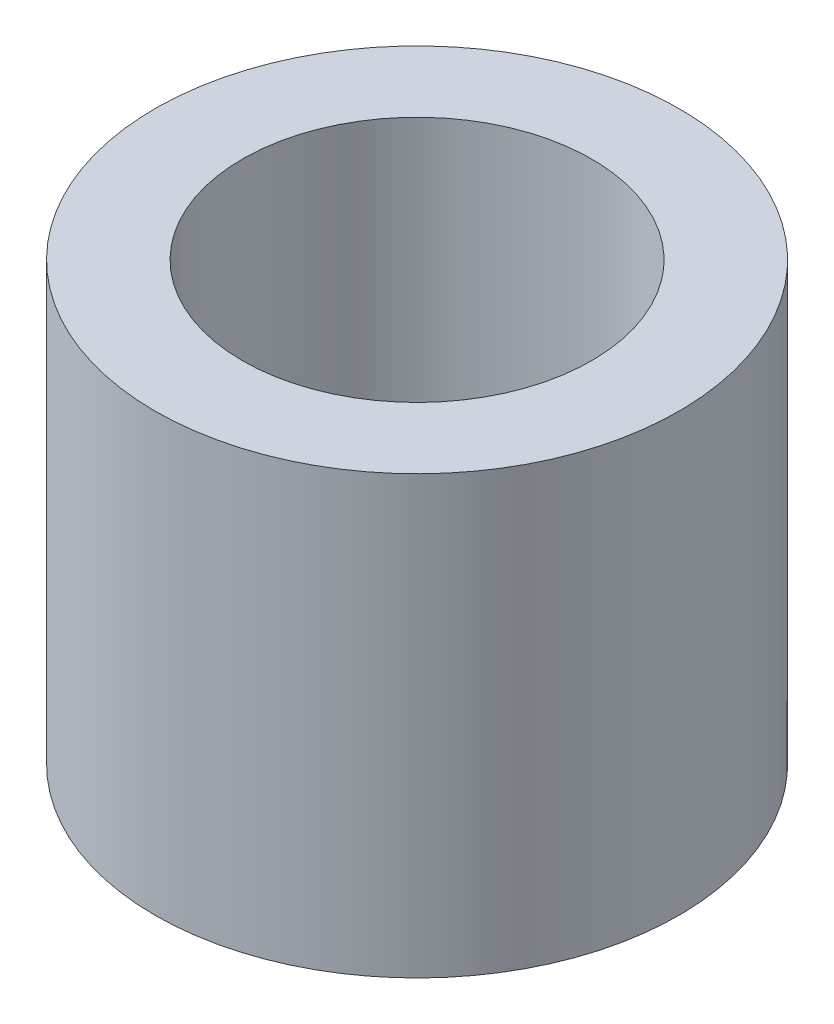
SolidWorks part; units mm, degrees
material "Brass"
ref_plane "Front Plane" through (0, 0, 0) normal (0, 0, 1) x (1, 0, 0)
ref_plane "Top Plane" through (0, 0, 0) normal (0, 1, 0) x (1, 0, 0)
ref_plane "Right Plane" through (0, 0, 0) normal (1, 0, 0) x (0, 0, -1)
sketch "Sketch2" plane through (0, 0, 0) normal (0, 1, 0) x (1, 0, 0)
  circle A0 centre (0, 0) radius 4
  circle A1 centre (0, 0) radius 6
extrude "Extrude1" add sketch "Sketch2" along normal blind 10
